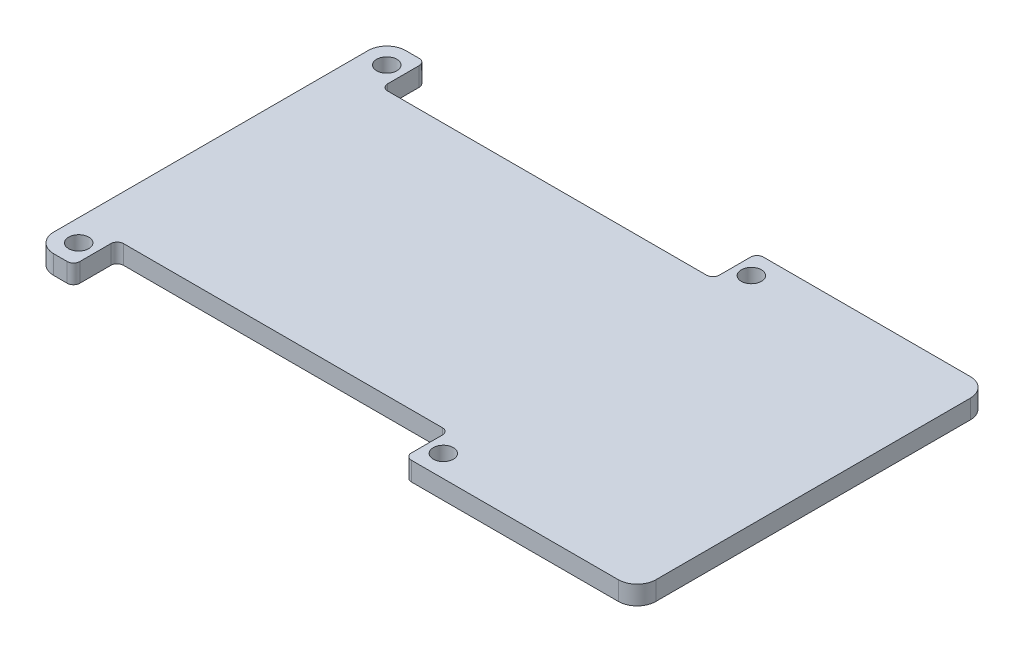
SolidWorks part; units mm, degrees
material "有机玻璃 (TM) GS 丙烯酸铸钣"
ref_plane "前视基准面" through (0, 0, 0) normal (0, 0, 1) x (1, 0, 0)
ref_plane "上视基准面" through (0, 0, 0) normal (0, 1, 0) x (1, 0, 0)
ref_plane "右视基准面" through (0, 0, 0) normal (1, 0, 0) x (0, 0, -1)
other "Configuration Table"
sketch "草图1" plane through (0, 0, 0) normal (0, 1, 0) x (1, 0, 0)
  line L0 (-21.1346, 23.39) -> (-21.1346, 18.3777)
  line L5 (-22.1346, 17.3777) -> (-72.8747, 17.3777)
  line L6 (-73.8747, 18.3777) -> (-73.8747, 23.39)
  line L7 (-22.1346, 21.0502) -> (-22.1346, 23.2653) construction
  line L12 (-80.009, 21.4027) -> (-80.009, -28.6044)
  line L13 (-77.0217, -31.5917) -> (12.7873, -31.5917)
  line L14 (15.7746, -28.6044) -> (15.7746, 21.4027)
  line L15 (12.7873, 24.39) -> (-77.0217, 24.39)
  line L16 (-80.009, 21.4027) -> (-80.009, -28.6044)
  line L17 (-77.0217, -31.5917) -> (-74.8747, -31.5917)
  line L18 (15.7746, -28.6044) -> (15.7746, 21.4027)
  line L19 (12.7873, 24.39) -> (-20.1346, 24.39)
  line L20 (-22.2671, 18.3777) -> (-24.4822, 18.3777) construction
  line L21 (-72.8747, 23.2653) -> (-72.8747, 21.0502) construction
  line L22 (-74.8747, 24.39) -> (-77.0217, 24.39)
  line L23 (-73.8747, 18.3777) -> (-73.8747, -36.7236) construction
  line L24 (-73.8747, -30.5917) -> (-73.8747, -25.645)
  line L25 (-72.8747, -24.645) -> (-22.1346, -24.645)
  line L26 (-21.1346, -25.645) -> (-21.1346, -30.5917)
  line L27 (-20.1346, -31.5917) -> (12.7873, -31.5917)
  arc A0 (-74.8747, 24.39) -> (-73.8747, 23.39) centre (-74.8747, 23.39) cw
  arc A1 (-73.8747, 18.3777) -> (-72.8747, 17.3777) centre (-72.8747, 18.3777) ccw
  arc A2 (-22.1346, 17.3777) -> (-21.1346, 18.3777) centre (-22.1346, 18.3777) ccw
  arc A3 (-21.1346, 23.39) -> (-20.1346, 24.39) centre (-20.1346, 23.39) cw
  circle A4 centre (-76.5285, 20.8867) radius 1.6
  circle A5 centre (-18.5286, 20.8866) radius 1.6
  circle A6 centre (-18.5283, -28.1137) radius 1.6
  circle A7 centre (-76.5283, -28.1135) radius 1.6
  arc A8 (-80.009, -28.6044) -> (-77.0217, -31.5917) centre (-77.0217, -28.6044) ccw
  arc A9 (12.7873, -31.5917) -> (15.7746, -28.6044) centre (12.7873, -28.6044) ccw
  arc A10 (15.7746, 21.4027) -> (12.7873, 24.39) centre (12.7873, 21.4027) ccw
  arc A11 (-77.0217, 24.39) -> (-80.009, 21.4027) centre (-77.0217, 21.4027) ccw
  arc A12 (-80.009, -28.6044) -> (-77.0217, -31.5917) centre (-77.0217, -28.6044) ccw
  arc A13 (12.7873, -31.5917) -> (15.7746, -28.6044) centre (12.7873, -28.6044) ccw
  arc A14 (15.7746, 21.4027) -> (12.7873, 24.39) centre (12.7873, 21.4027) ccw
  arc A15 (-77.0217, 24.39) -> (-80.009, 21.4027) centre (-77.0217, 21.4027) ccw
  arc A20 (-74.8747, -31.5917) -> (-73.8747, -30.5917) centre (-74.8747, -30.5917) ccw
  arc A21 (-73.8747, -25.645) -> (-72.8747, -24.645) centre (-72.8747, -25.645) cw
  arc A22 (-22.1346, -24.645) -> (-21.1346, -25.645) centre (-22.1346, -25.645) cw
  arc A23 (-21.1346, -30.5917) -> (-20.1346, -31.5917) centre (-20.1346, -30.5917) ccw
  point P49 (-73.8747, -31.5917)
  point P52 (-73.8747, -24.645)
  point P57 (-21.1346, -31.5917)
  dimension "D2" = 3.2
  dimension "D3" = 3.2
  dimension "D4" = 3.2
  dimension "D5" = 3.2
  dimension "D6" = 1
  dimension "D7" = 1
  dimension "D9" = 1
  dimension "D10" = 1
  dimension "D1" = 0
  dimension "D8" = 1
extrude "凸台-拉伸1" add sketch "草图1" along normal blind 3
